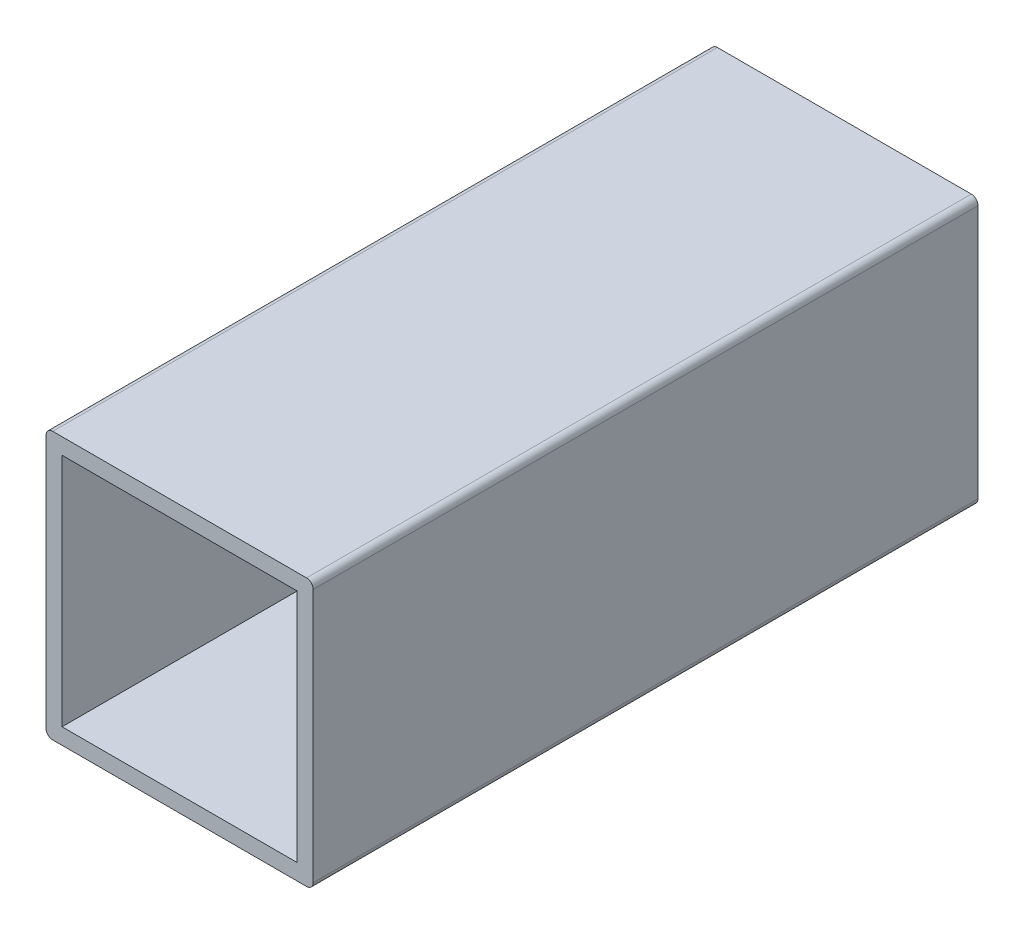
SolidWorks part; units mm, degrees
material "AISI 1020"
ref_plane "Plano frontal" through (0, 0, 0) normal (0, 0, 1) x (1, 0, 0)
ref_plane "Plano superior" through (0, 0, 0) normal (0, 1, 0) x (1, 0, 0)
ref_plane "Plano direito" through (0, 0, 0) normal (1, 0, 0) x (0, 0, -1)
sketch "Esboço1" plane through (0, 0, 0) normal (0, 0, 1) x (1, 0, 0)
  line L0 (-35.2, 35.2) -> (35.2, 35.2)
  line L1 (-38, -40) -> (38, -40)
  line L2 (-40, -38) -> (-40, 38)
  line L3 (-38, 40) -> (38, 40)
  line L4 (40, -38) -> (40, 38)
  line L5 (-40, -40) -> (40, 40) construction
  line L6 (-40, 40) -> (40, -40) construction
  line L7 (35.2, -35.2) -> (35.2, 35.2)
  line L8 (-35.2, -35.2) -> (35.2, -35.2)
  line L9 (-35.2, -35.2) -> (-35.2, 35.2)
  arc A0 (-40, -38) -> (-38, -40) centre (-38, -38) ccw
  arc A1 (38, -40) -> (40, -38) centre (38, -38) ccw
  arc A2 (38, 40) -> (40, 38) centre (38, 38) cw
  arc A3 (-38, 40) -> (-40, 38) centre (-38, 38) ccw
  arc A4 (35.2, 35.2) -> (35.2, 35.2) centre (35.2, 35.2) cw
  arc A5 (35.2, -35.2) -> (35.2, -35.2) centre (35.2, -35.2) ccw
  arc A6 (-35.2, -35.2) -> (-35.2, -35.2) centre (-35.2, -35.2) ccw
  arc A7 (-35.2, 35.2) -> (-35.2, 35.2) centre (-35.2, 35.2) ccw
  point P0 (0, 0)
  dimension "D3" = 2
  dimension "D1" = 80
  dimension "D2" = 80
  dimension "D4" = 4.8
extrude "Ressalto-extrusão1" add sketch "Esboço1" against normal mid plane 199
